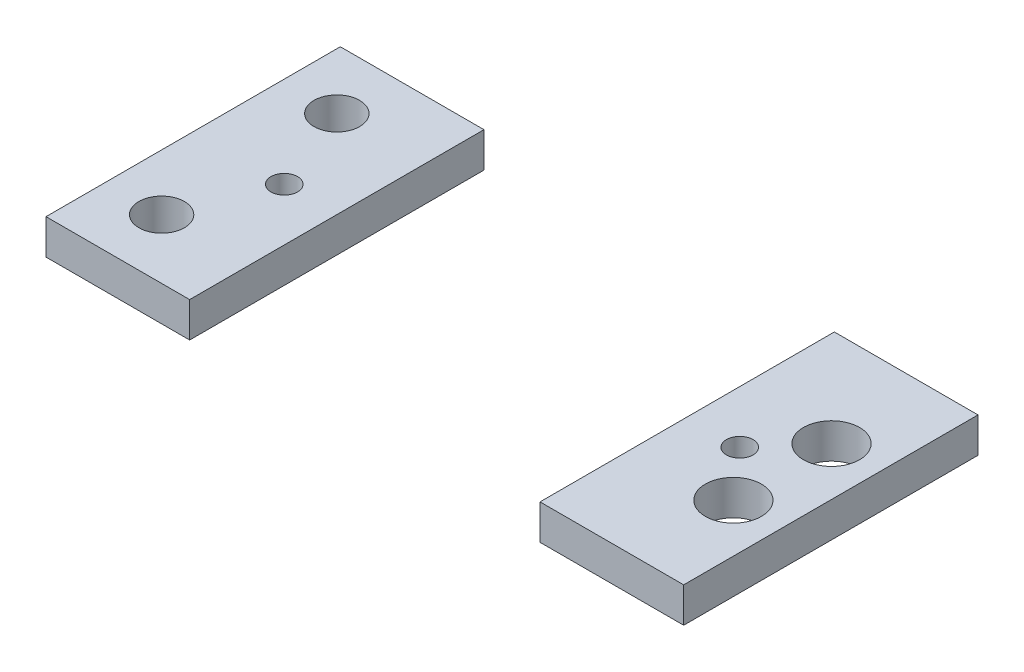
SolidWorks part; units mm, degrees
ref_plane "정면" through (0, 0, 0) normal (0, 0, 1) x (1, 0, 0)
ref_plane "윗면" through (0, 0, 0) normal (0, 1, 0) x (1, 0, 0)
ref_plane "우측면" through (0, 0, 0) normal (1, 0, 0) x (0, 0, -1)
sketch "스케치1" plane through (0, 0, 0) normal (0, 1, 0) x (1, 0, 0)
  line L1 (0, 0) -> (91, 0)
  line L2 (0, 0) -> (0, 42)
  line L3 (0, 42) -> (91, 42)
  line L4 (91, 0) -> (91, 42)
  dimension "D1" = 91
  dimension "D2" = 42
extrude "보스-돌출1" add sketch "스케치1" along normal blind 5
sketch "스케치2" plane through (0, 5, 0) normal (0, 1, 0) x (1, 0, 0)
  line L0 (0, 42) -> (0, 0) construction
  line L1 (8, 33.5) -> (28, 33.5) construction
  line L2 (8, 33.5) -> (8, 8.5) construction
  line L3 (8, 8.5) -> (28, 8.5) construction
  line L4 (28, 33.5) -> (28, 8.5) construction
  line L5 (91, 42) -> (0, 42) construction
  line L7 (84.0949, 28) -> (84.0949, 42) construction
  line L8 (42.0949, 28) -> (84.0949, 28) construction
  line L9 (42.0949, 28) -> (42.0949, 14) construction
  line L10 (42.0949, 14) -> (84.0949, 14) construction
  line L11 (84.0949, 28) -> (84.0949, 14) construction
  line L12 (84.0949, 14) -> (84.0949, 0) construction
  line L13 (0, 0) -> (91, 0) construction
  line L14 (91, 21) -> (78, 21) construction
  line L15 (91, 0) -> (91, 42) construction
  line L16 (78, 21) -> (13, 21) construction
  line L17 (13, 21) -> (0, 21) construction
  circle A0 centre (28, 33.5) radius 1.75
  circle A1 centre (28, 8.5) radius 1.75
  circle A2 centre (8, 8.5) radius 1.75
  circle A3 centre (8, 33.5) radius 1.75
  circle A4 centre (42.0949, 28) radius 2.25
  circle A5 centre (42.0949, 14) radius 2.25
  circle A6 centre (84.0949, 14) radius 2.25
  circle A7 centre (84.0949, 28) radius 2.25
  circle A8 centre (78, 21) radius 1.9
  circle A9 centre (13, 21) radius 1.9
  dimension "D5" = 3.5
  dimension "D8" = 4.5
  dimension "D10" = 3.8
  dimension "D1" = 8
  dimension "D2" = 8.5
  dimension "D3" = 25
  dimension "D4" = 20
  dimension "D6" = 14
  dimension "D7" = 42
  dimension "D9" = 65
extrude "컷-돌출1" cut sketch "스케치2" against normal blind 5
sketch "스케치3" plane through (0, 5, 0) normal (0, 1, 0) x (1, 0, 0)
  circle A0 centre (84.0949, 28) radius 4
  circle A1 centre (84.0949, 14) radius 4
  circle A2 centre (42.0949, 14) radius 4
  circle A3 centre (42.0949, 28) radius 4
  circle A4 centre (28, 33.5) radius 3.25
  circle A5 centre (28, 8.5) radius 3.25
  circle A6 centre (8, 8.5) radius 3.25
  circle A7 centre (8, 33.5) radius 3.25
  dimension "D1" = 8
  dimension "D2" = 6.5
extrude "컷-돌출2" cut sketch "스케치3" against normal blind 5
sketch "스케치4" plane through (0, 5, 0) normal (0, 1, 0) x (1, 0, 0)
  line L0 (91, 42) -> (0, 42) construction
  line L1 (20.5, 42) -> (70.5, 42)
  line L2 (20.5, 42) -> (20.5, 0)
  line L3 (20.5, 0) -> (70.5, 0)
  line L4 (70.5, 42) -> (70.5, 0)
  line L5 (0, 0) -> (91, 0) construction
  line L6 (91, 21) -> (70.5, 21) construction
  line L7 (91, 0) -> (91, 42) construction
  line L8 (20.5, 21) -> (0, 21) construction
  line L9 (0, 42) -> (0, 0) construction
  dimension "D1" = 50
extrude "컷-돌출3" cut sketch "스케치4" against normal blind 10
